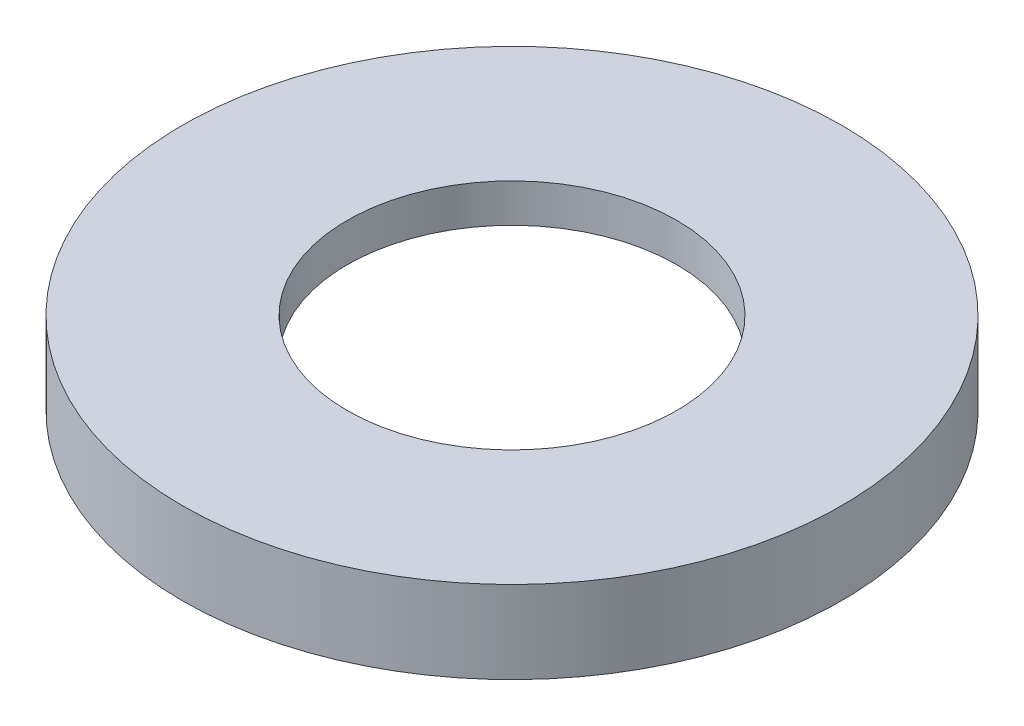
SolidWorks part; units mm, degrees
ref_plane "Front Plane" through (0, 0, 0) normal (0, 0, 1) x (1, 0, 0)
ref_plane "Top Plane" through (0, 0, 0) normal (0, 1, 0) x (1, 0, 0)
ref_plane "Right Plane" through (0, 0, 0) normal (1, 0, 0) x (0, 0, -1)
sketch "Sketch1" plane through (0, 0, 0) normal (1, 0, 0) x (0, 0, -1)
  line L0 (0, -462.6966) -> (0, 22672.1332) construction
  line L1 (-11.25, -2.9386) -> (-11.25, -4.9386)
  line L4 (-11.25, -2.9386) -> (-7.5, -2.9386)
  line L5 (-7.5, -1.1886) -> (-7.5, -2.9386)
  line L7 (-15, -4.9386) -> (-15, -1.1886)
  line L10 (-15, -4.9386) -> (-11.25, -4.9386)
  line L12 (-15, -1.1886) -> (-7.5, -1.1886)
  dimension "D1" = 15
  dimension "D2" = 3.75
  dimension "D3" = 3.75
  dimension "D4" = 2
  dimension "D5" = 1.75
revolve "Revolve1" add sketch "Sketch1" angle 360 about L0
